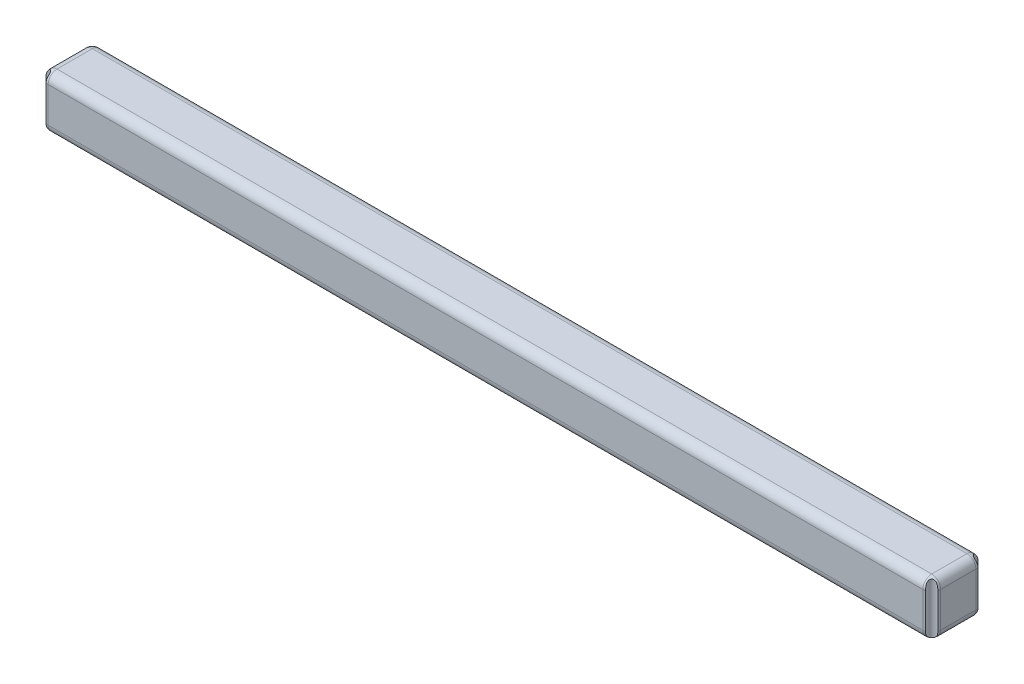
SolidWorks part; units mm, degrees
ref_plane "Front Plane" through (0, 0, 0) normal (0, 0, 1) x (1, 0, 0)
ref_plane "Top Plane" through (0, 0, 0) normal (0, 1, 0) x (1, 0, 0)
ref_plane "Right Plane" through (0, 0, 0) normal (1, 0, 0) x (0, 0, -1)
sketch "Sketch1" plane through (0, 0, 0) normal (0, 0, 1) x (1, 0, 0)
  line L1 (0, 0) -> (100, 0)
  line L2 (0, 0) -> (0, 5.95)
  line L3 (0, 5.95) -> (100, 5.95)
  line L4 (100, 0) -> (100, 5.95)
  dimension "D1" = 5.95
  dimension "D2" = 100
extrude "Boss-Extrude1" add sketch "Sketch1" along normal blind 5.95
fillet "Fillet1" radius 1 12 edges at (0, 2.975, 0) (50, 0, 0) (100, 2.975, 0) (50, 5.95, 0) (0, 2.975, 5.95) (50, 0, 5.95) (100, 2.975, 5.95) (0, 5.95, 2.975) (100, 5.95, 2.975) (100, 0, 2.975) (0, 0, 2.975) (50, 5.95, 5.95)
sketch "Sketch2" plane through (0, 5.95, 0) normal (0, 1, 0) x (1, 0, 0)
  circle A0 centre (99.7071, -0.2929) radius 0.5
  arc A1 (100, -1) -> (99, 0) centre (99, -1) ccw construction
  circle A2 centre (99.7071, -5.6571) radius 0.5
  arc A3 (99, -5.95) -> (100, -4.95) centre (99, -4.95) ccw construction
  circle A4 centre (0.2929, -0.2929) radius 0.5
  arc A5 (1, 0) -> (0, -1) centre (1, -1) ccw construction
  circle A6 centre (0.2929, -5.6571) radius 0.5
  arc A7 (0, -4.95) -> (1, -5.95) centre (1, -4.95) ccw construction
  dimension "D1" = 1
  dimension "D2" = 1
extrude "Cut-Extrude1" cut sketch "Sketch2" against normal blind 10
